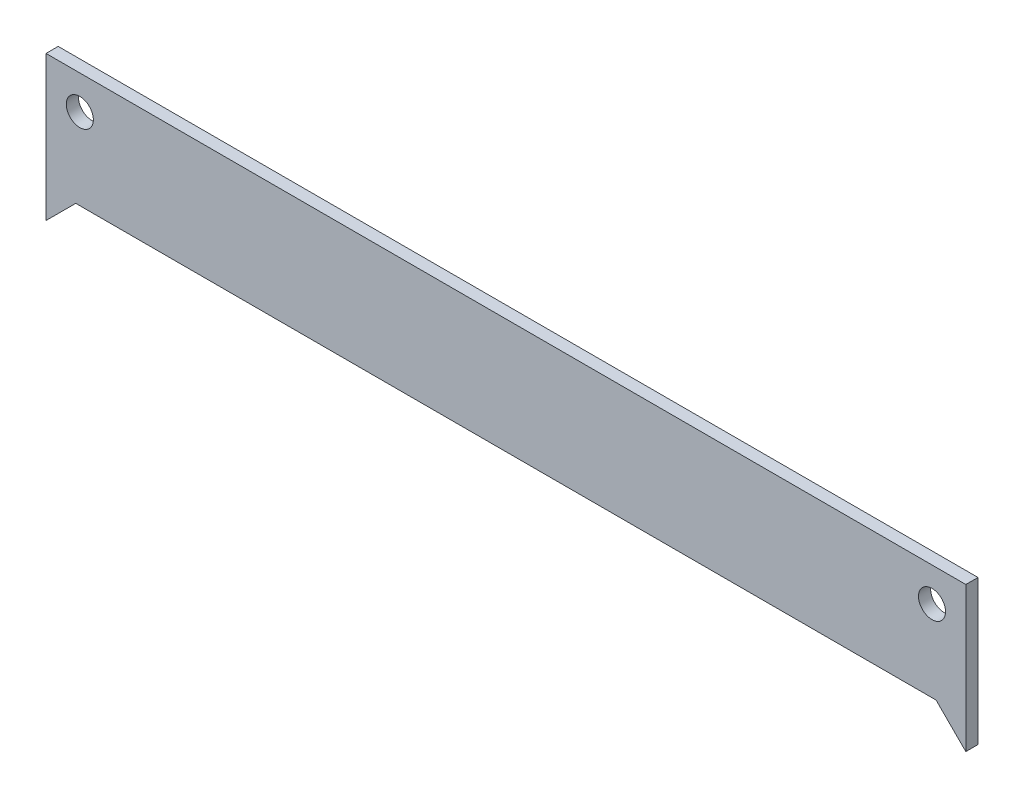
SolidWorks part; units mm, degrees
ref_plane "Alzado" through (0, 0, 0) normal (0, 0, 1) x (1, 0, 0)
ref_plane "Planta" through (0, 0, 0) normal (0, 1, 0) x (1, 0, 0)
ref_plane "Vista lateral" through (0, 0, 0) normal (1, 0, 0) x (0, 0, -1)
sketch "Croquis1" plane through (0, 0, 0) normal (0, 0, 1) x (1, 0, 0)
  line L0 (-49.1437, 1.3678) -> (-49.1437, -0.8322)
  line L1 (-49.1437, 9.8678) -> (18.8563, 9.8678)
  line L2 (-49.1437, 9.8678) -> (-49.1437, 1.3678)
  line L4 (18.8563, 9.8678) -> (18.8563, 1.3678)
  line L5 (-49.1437, -0.8322) -> (-46.9437, 1.3678)
  line L6 (18.8563, 1.3678) -> (18.8563, -0.8322)
  line L7 (18.8563, -0.8322) -> (16.6563, 1.3678)
  line L8 (16.6563, 1.3678) -> (-46.9437, 1.3678)
  circle A0 centre (-46.6437, 7.3678) radius 1
  circle A1 centre (16.3563, 7.3678) radius 1
  dimension "D3" = 2.5
  dimension "D1" = 8.5
  dimension "D2" = 68
  dimension "D4" = 2.5
  dimension "D5" = 2.5
  dimension "D6" = 2.5
extrude "Saliente-Extruir1" add sketch "Croquis1" along normal blind 0.9
